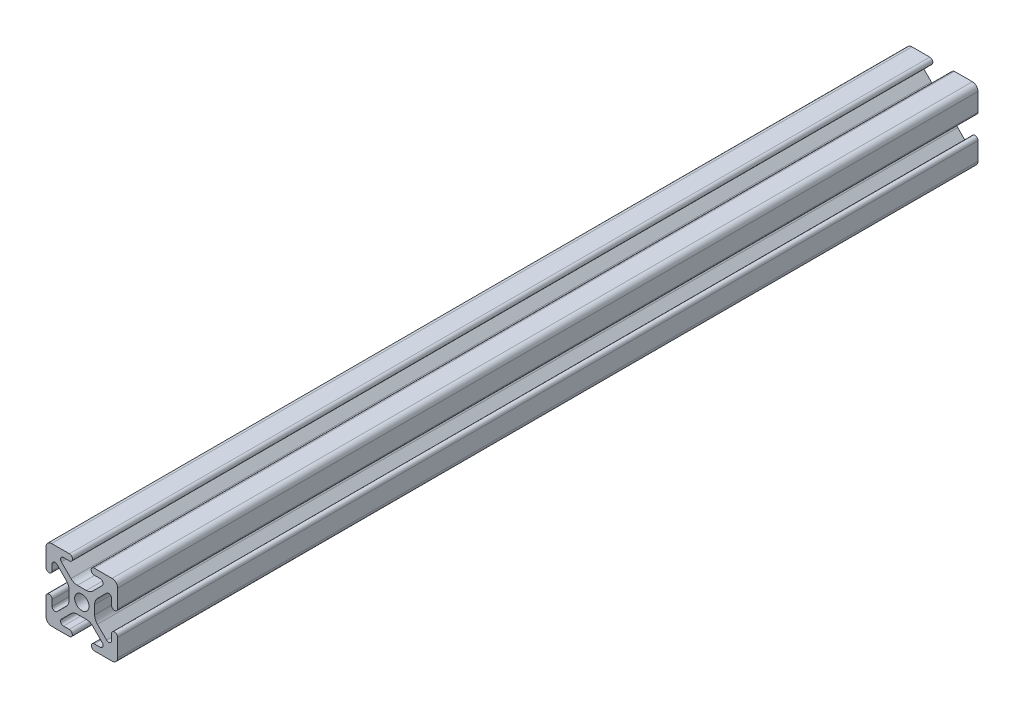
SolidWorks part; units mm, degrees
material "6061 Alloy"
ref_plane "Front Plane" through (0, 0, 0) normal (0, 0, 1) x (1, 0, 0)
ref_plane "Top Plane" through (0, 0, 0) normal (0, 1, 0) x (1, 0, 0)
ref_plane "Right Plane" through (0, 0, 0) normal (1, 0, 0) x (0, 0, -1)
sketch "Sketch1" plane through (0, 0, 0) normal (0, 0, 1) x (1, 0, 0)
  line L0 (-8.6363, 7.1116) -> (-5.4322, 3.9121)
  line L1 (-4.455, 1.5554) -> (-4.455, -1.5554)
  line L2 (-5.4322, -3.9121) -> (-8.6363, -7.1116)
  line L3 (-10.36, -6.3969) -> (-10.36, -4.32)
  line L4 (-12.5, -4.32) -> (-12.5, -8.6518)
  line L5 (-12.5, -8.6518) -> (-12.5, -10.5371)
  line L6 (-10.5371, -12.5) -> (-8.4416, -12.5)
  line L7 (-8.4416, -12.5) -> (-4.3879, -12.5)
  line L8 (-4.3879, -10.36) -> (-6.42, -10.36)
  line L9 (-7.1337, -8.6353) -> (-3.7953, -5.3018)
  line L10 (-1.5554, -4.375) -> (1.5554, -4.375)
  line L11 (10.36, 4.32) -> (10.36, 6.3969)
  line L12 (12.5, 7.9913) -> (12.5, 4.32)
  line L13 (12.5, 10.5371) -> (12.5, 7.9913)
  line L14 (4.32, 12.5) -> (10.5371, 12.5)
  line L16 (6.42, 10.36) -> (4.32, 10.36)
  line L17 (3.7953, 5.3018) -> (7.1337, 8.6353)
  line L18 (7.1337, -8.6353) -> (3.7953, -5.3018)
  line L19 (4.3879, -10.36) -> (6.42, -10.36)
  line L20 (8.4416, -12.5) -> (4.3879, -12.5)
  line L21 (10.5371, -12.5) -> (8.4416, -12.5)
  line L22 (12.5, -8.6518) -> (12.5, -10.5371)
  line L23 (12.5, -4.32) -> (12.5, -8.6518)
  line L24 (10.36, -6.3969) -> (10.36, -4.32)
  line L25 (5.4322, -3.9121) -> (8.6363, -7.1116)
  line L26 (4.455, 1.5554) -> (4.455, -1.5554)
  line L27 (8.6363, 7.1116) -> (5.4322, 3.9121)
  line L28 (1.5554, 4.375) -> (-1.5554, 4.375)
  line L29 (-3.7953, 5.3018) -> (-7.1337, 8.6353)
  line L30 (-6.42, 10.36) -> (-4.32, 10.36)
  line L32 (-4.32, 12.5) -> (-10.5371, 12.5)
  line L33 (-12.5, 10.5371) -> (-12.5, 7.9913)
  line L34 (-12.5, 7.9913) -> (-12.5, 4.32)
  line L35 (-10.36, 4.32) -> (-10.36, 6.3969)
  line L36 (-15.7693, 0) -> (12.5, 0) construction
  line L37 (0, 13.9334) -> (0, -12.3541) construction
  circle A0 centre (0, 0) radius 2.5
  arc A1 (-8.6363, 7.1116) -> (-10.36, 6.3969) centre (-9.35, 6.3969) ccw
  arc A2 (-4.455, 1.5554) -> (-5.4322, 3.9121) centre (-7.7855, 1.5554) ccw
  arc A3 (-5.4322, -3.9121) -> (-4.455, -1.5554) centre (-7.7855, -1.5554) ccw
  arc A4 (-10.36, -6.3969) -> (-8.6363, -7.1116) centre (-9.35, -6.3969) ccw
  arc A5 (-10.36, -4.32) -> (-12.5, -4.32) centre (-11.43, -4.32) ccw
  arc A6 (-12.5, -10.5371) -> (-10.5371, -12.5) centre (-10.5371, -10.5371) ccw
  arc A7 (-4.3879, -12.5) -> (-4.3879, -10.36) centre (-4.3879, -11.43) ccw
  arc A8 (-7.1337, -8.6353) -> (-6.42, -10.36) centre (-6.42, -9.35) ccw
  arc A9 (-1.5554, -4.375) -> (-3.7953, -5.3018) centre (-1.5554, -7.545) ccw
  arc A10 (12.5, 4.32) -> (10.36, 4.32) centre (11.43, 4.32) cw
  arc A11 (10.5371, 12.5) -> (12.5, 10.5371) centre (10.5371, 10.5371) cw
  arc A12 (4.32, 10.36) -> (4.32, 12.5) centre (4.32, 11.43) cw
  arc A13 (6.42, 10.36) -> (7.1337, 8.6353) centre (6.42, 9.35) cw
  arc A14 (3.7953, 5.3018) -> (1.5554, 4.375) centre (1.5554, 7.545) cw
  arc A15 (1.5554, -4.375) -> (3.7953, -5.3018) centre (1.5554, -7.545) cw
  arc A16 (7.1337, -8.6353) -> (6.42, -10.36) centre (6.42, -9.35) cw
  arc A17 (4.3879, -12.5) -> (4.3879, -10.36) centre (4.3879, -11.43) cw
  arc A18 (12.5, -10.5371) -> (10.5371, -12.5) centre (10.5371, -10.5371) cw
  arc A19 (10.36, -4.32) -> (12.5, -4.32) centre (11.43, -4.32) cw
  arc A20 (10.36, -6.3969) -> (8.6363, -7.1116) centre (9.35, -6.3969) cw
  arc A21 (5.4322, -3.9121) -> (4.455, -1.5554) centre (7.7855, -1.5554) cw
  arc A22 (4.455, 1.5554) -> (5.4322, 3.9121) centre (7.7855, 1.5554) cw
  arc A23 (8.6363, 7.1116) -> (10.36, 6.3969) centre (9.35, 6.3969) cw
  arc A24 (-3.7953, 5.3018) -> (-1.5554, 4.375) centre (-1.5554, 7.545) ccw
  arc A25 (-6.42, 10.36) -> (-7.1337, 8.6353) centre (-6.42, 9.35) ccw
  arc A26 (-4.32, 10.36) -> (-4.32, 12.5) centre (-4.32, 11.43) ccw
  arc A27 (-10.5371, 12.5) -> (-12.5, 10.5371) centre (-10.5371, 10.5371) ccw
  arc A28 (-12.5, 4.32) -> (-10.36, 4.32) centre (-11.43, 4.32) ccw
  dimension "D4" = 14.86
  dimension "D5" = 2.14
  dimension "D6" = 6.5
  dimension "D7" = 8.75
  dimension "D8" = 1.01
  dimension "D9" = 3.17
  dimension "D14" = 5
  dimension "D1" = 25
  dimension "D2" = 8.91
  dimension "D3" = 12.5
  dimension "D12" = 2.14
extrude "Extrude1" add sketch "Sketch1" against normal blind 300
